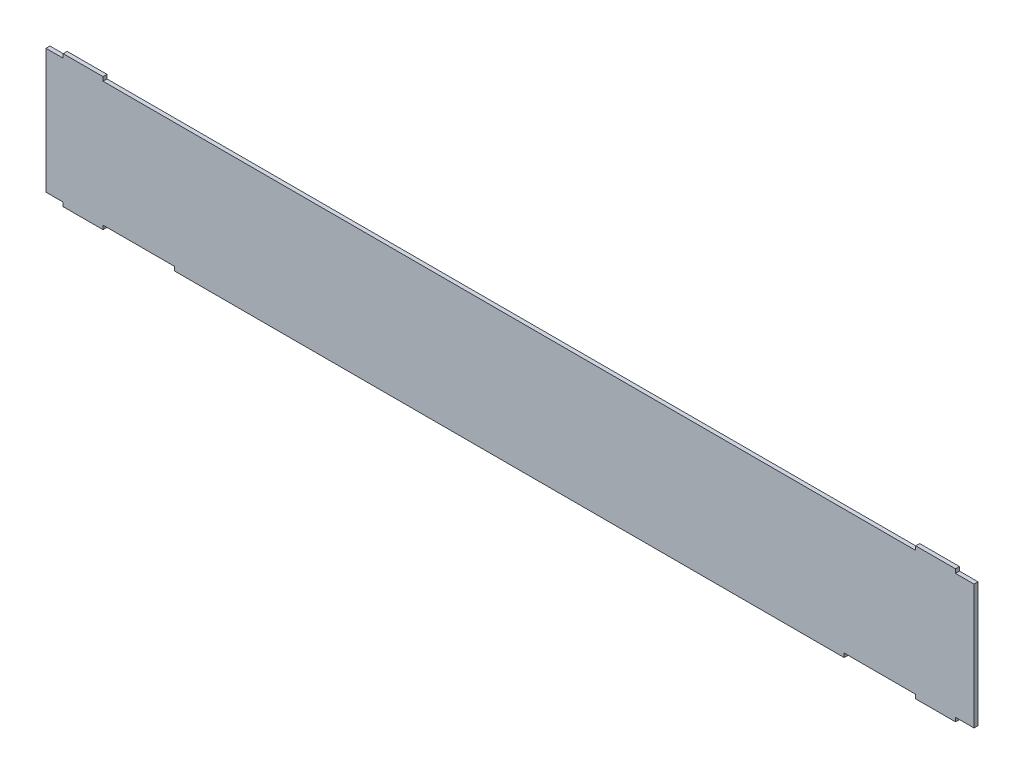
SolidWorks part; units mm, degrees
material "Balsa"
ref_plane "Alzado" through (0, 0, 0) normal (0, 0, 1) x (1, 0, 0)
ref_plane "Planta" through (0, 0, 0) normal (0, 1, 0) x (1, 0, 0)
ref_plane "Vista lateral" through (0, 0, 0) normal (1, 0, 0) x (0, 0, -1)
sketch "Sketch1" plane through (0, 0, 0) normal (0, 0, 1) x (1, 0, 0)
  line L1 (0, 0) -> (700, 0)
  line L2 (0, 0) -> (0, 100)
  line L3 (0, 100) -> (700, 100)
  line L4 (700, 0) -> (700, 100)
  dimension "D1" = 700
  dimension "D2" = 100
extrude "Boss-Extrude1" add sketch "Sketch1" along normal blind 3
sketch "Sketch11" plane through (0, 0, 0) normal (0, 0, -1) x (-1, 0, 0)
  line L1 (-700, 0) -> (-686, 0)
  line L2 (-700, 0) -> (-700, 3)
  line L3 (-700, 3) -> (-686, 3)
  line L4 (-686, 0) -> (-686, 3)
  dimension "D1" = 14
  dimension "D2" = 3
extrude "Cut-Extrude8" cut sketch "Sketch11" against normal blind 10
sketch "Sketch12" plane through (0, 0, 0) normal (0, 0, -1) x (-1, 0, 0)
  line L0 (0, 0) -> (-686, 0) construction
  line L1 (-656, 0) -> (-602, 0)
  line L2 (-656, 0) -> (-656, 3)
  line L3 (-656, 3) -> (-602, 3)
  line L4 (-602, 0) -> (-602, 3)
  line L5 (-700, 3) -> (-700, 100) construction
  dimension "D1" = 54
  dimension "D2" = 3
  dimension "D3" = 44
extrude "Cut-Extrude9" cut sketch "Sketch12" against normal blind 10
sketch "Sketch13" plane through (0, 0, 0) normal (0, 0, -1) x (-1, 0, 0)
  line L1 (0, 0) -> (-13, 0)
  line L2 (0, 0) -> (0, 3)
  line L3 (0, 3) -> (-13, 3)
  line L4 (-13, 0) -> (-13, 3)
  dimension "D1" = 13
  dimension "D2" = 3
extrude "Cut-Extrude10" cut sketch "Sketch13" against normal blind 10
sketch "Sketch14" plane through (0, 0, 0) normal (0, 0, -1) x (-1, 0, 0)
  line L0 (-13, 0) -> (-602, 0) construction
  line L1 (-43, 0) -> (-97, 0)
  line L2 (-43, 0) -> (-43, 3)
  line L3 (-43, 3) -> (-97, 3)
  line L4 (-97, 0) -> (-97, 3)
  line L5 (0, 100) -> (0, 3) construction
  dimension "D1" = 54
  dimension "D2" = 3
  dimension "D3" = 43
extrude "Cut-Extrude11" cut sketch "Sketch14" against normal blind 10
sketch "Sketch15" plane through (0, 0, 0) normal (0, 0, -1) x (-1, 0, 0)
  line L1 (-700, 100) -> (-686, 100)
  line L2 (-700, 100) -> (-700, 97)
  line L3 (-700, 97) -> (-686, 97)
  line L4 (-686, 100) -> (-686, 97)
  dimension "D1" = 3
  dimension "D2" = 14
extrude "Cut-Extrude12" cut sketch "Sketch15" against normal blind 10
sketch "Sketch16" plane through (0, 0, 0) normal (0, 0, -1) x (-1, 0, 0)
  line L0 (-686, 100) -> (0, 100) construction
  line L1 (-656, 100) -> (-602, 100)
  line L2 (-656, 100) -> (-656, 97)
  line L3 (-656, 97) -> (-602, 97)
  line L4 (-602, 100) -> (-602, 97)
  line L5 (-700, 3) -> (-700, 97) construction
  dimension "D1" = 3
  dimension "D2" = 54
  dimension "D3" = 44
extrude "Cut-Extrude13" cut sketch "Sketch16" against normal blind 10
sketch "Sketch17" plane through (0, 0, 0) normal (0, 0, -1) x (-1, 0, 0)
  line L1 (0, 100) -> (-13, 100)
  line L2 (0, 100) -> (0, 97)
  line L3 (0, 97) -> (-13, 97)
  line L4 (-13, 100) -> (-13, 97)
  dimension "D1" = 13
  dimension "D2" = 3
extrude "Cut-Extrude14" cut sketch "Sketch17" against normal blind 10
sketch "Sketch18" plane through (0, 0, 0) normal (0, 0, -1) x (-1, 0, 0)
  line L0 (-602, 100) -> (-13, 100) construction
  line L1 (-43, 100) -> (-97, 100)
  line L2 (-43, 100) -> (-43, 97)
  line L3 (-43, 97) -> (-97, 97)
  line L4 (-97, 100) -> (-97, 97)
  line L5 (0, 97) -> (0, 3) construction
  dimension "D1" = 3
  dimension "D2" = 54
  dimension "D3" = 43
extrude "Cut-Extrude15" cut sketch "Sketch18" against normal blind 10
sketch "Sketch21" plane through (0, 0, 3) normal (0, 0, 1) x (1, 0, 0)
  line L1 (97, 100) -> (602, 100)
  line L2 (97, 100) -> (97, 97)
  line L3 (97, 97) -> (602, 97)
  line L4 (602, 100) -> (602, 97)
extrude "Cut-Extrude16" cut sketch "Sketch21" against normal blind 3
